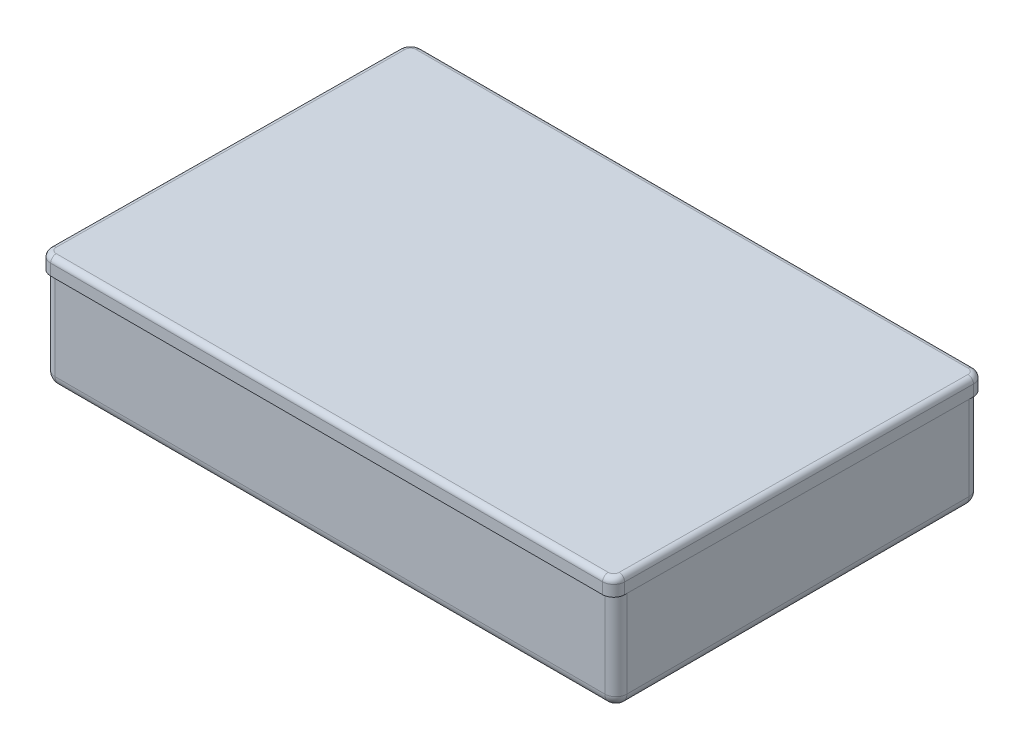
SolidWorks part; units mm, degrees
material "Acrylic (Medium-high impact)"
ref_plane "Front" through (0, 0, 0) normal (0, 0, 1) x (1, 0, 0)
ref_plane "Top" through (0, 0, 0) normal (0, 1, 0) x (1, 0, 0)
ref_plane "Right" through (0, 0, 0) normal (1, 0, 0) x (0, 0, -1)
sketch "Sketch1" plane through (0, 0, 0) normal (0, 1, 0) x (1, 0, 0)
  line L1 (-164.465, 104.775) -> (164.465, 104.775)
  line L2 (-164.465, 104.775) -> (-164.465, -104.775)
  line L3 (-164.465, -104.775) -> (164.465, -104.775)
  line L4 (164.465, 104.775) -> (164.465, -104.775)
  line L5 (-164.465, 104.775) -> (164.465, -104.775) construction
  line L6 (-164.465, -104.775) -> (164.465, 104.775) construction
  point P0 (0, 0)
  dimension "D1" = 328.93
  dimension "D2" = 209.55
extrude "Boss-Extrude1" add sketch "Sketch1" along normal blind 57.15
fillet "Fillet1" radius 6.35 8 edges at (0, 0, -104.775) (-164.465, 0, 0) (0, 0, 104.775) (164.465, 0, 0) (-164.465, 28.575, -104.775) (164.465, 28.575, -104.775) (164.465, 28.575, 104.775) (-164.465, 28.575, 104.775)
shell "Shell1" thickness 2.54
sketch "Sketch2" plane through (0, 0, 0) normal (1, 0, 0) x (0, 0, -1)
  line L0 (104.775, 57.15) -> (106.5711, 55.3539) construction
  line L2 (106.5711, 55.3539) -> (-106.7808, 57.2158)
  line L3 (-106.7808, 57.2158) -> (-106.6977, 66.7405)
  line L4 (-106.6977, 66.7405) -> (106.6542, 64.8786)
  line L5 (106.5711, 55.3539) -> (106.6542, 64.8786)
  line L6 (104.775, 57.15) -> (104.775, 55.3539) construction
  line L7 (104.775, 55.3539) -> (106.5711, 55.3539) construction
  line L8 (-98.425, 57.15) -> (98.425, 57.15) construction
  dimension "D1" = 2.54
  dimension "D2" = 9.525
  dimension "D3" = 213.36
  dimension "D4" = 0.5
extrude "LID OPENING ANGLE CONTROL" add sketch "Sketch2" along normal mid plane 330.2 separate body
fillet "Fillet2" radius 6.35 4 edges at (165.1, 60.1163, -106.6126) (-165.1, 60.1163, -106.6126) (165.1, 61.9782, 106.7393) (-165.1, 61.9782, 106.7393)
fillet "Fillet3" radius 3.175 8 edges at (163.2401, 66.7242, 104.8379) (0, 66.7405, 106.6977) (-163.2401, 66.7242, 104.8379) (-165.1, 65.8095, 0.0218) (-163.2401, 64.8948, -104.7944) (0, 64.8786, -106.6542) (163.2401, 64.8948, -104.7944) (165.1, 65.8095, 0.0218)
shell "Shell2" thickness 2.54
